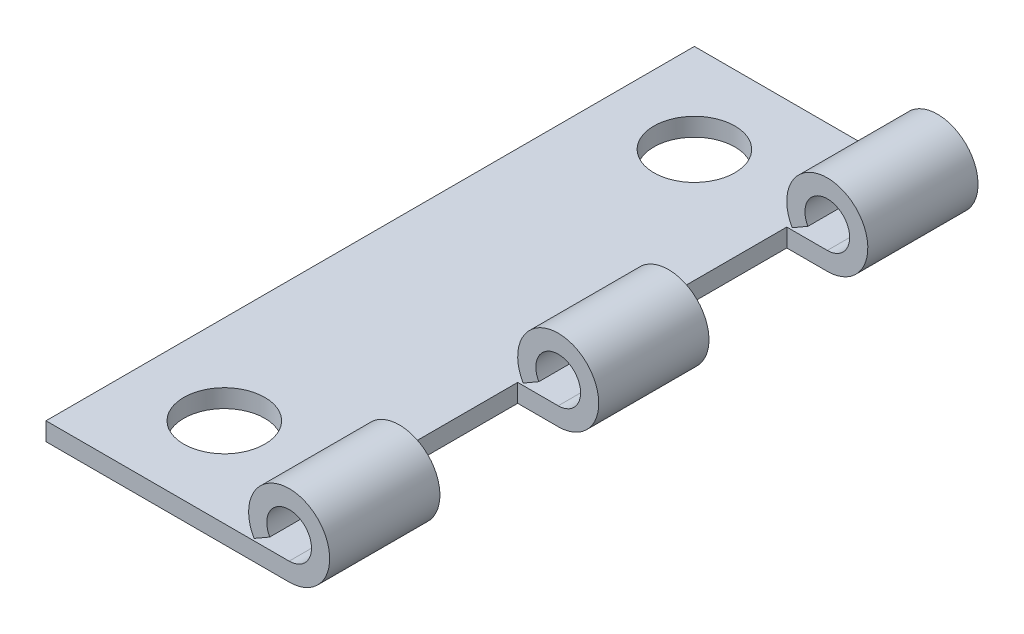
SolidWorks part; units mm, degrees
ref_plane "Front Plane" through (0, 0, 0) normal (0, 0, 1) x (1, 0, 0)
ref_plane "Top Plane" through (0, 0, 0) normal (0, 1, 0) x (1, 0, 0)
ref_plane "Right Plane" through (0, 0, 0) normal (1, 0, 0) x (0, 0, -1)
sketch "Sketch1" plane through (0, 0, 0) normal (0, 0, 1) x (1, 0, 0)
  line L0 (0, 0) -> (19.05, 0)
  line L1 (16.3004, 1.5875) -> (17.5322, 2.2987)
  line L2 (19.05, 1.4224) -> (0, 1.4224)
  line L3 (0, 1.4224) -> (0, 0)
  line L4 (19.05, 1.4224) -> (19.05, 10.3225) construction
  arc A0 (19.05, 0) -> (16.3004, 1.5875) centre (19.05, 3.175) ccw
  arc A1 (17.5322, 2.2987) -> (19.05, 1.4224) centre (19.05, 3.175) cw
  dimension "D1" = 1.4224
  dimension "D3" = 120
  dimension "D5" = 3.175
  dimension "D2" = 1.4224
  dimension "D4" = 19.05
extrude "Boss-Extrude1" add sketch "Sketch1" along normal blind 50.8
sketch "Sketch2" plane through (0, 0, 0) normal (0, -1, 0) x (1, 0, 0)
  line L0 (0, 50.8) -> (0, 0) construction
  line L1 (0, 50.8) -> (19.05, 50.8) construction
  line L2 (0, 0) -> (19.05, 0) construction
  line L3 (22.225, 0) -> (22.225, 50.8) construction
  line L4 (15.875, 50.8) -> (22.225, 50.8)
  line L5 (15.875, 50.8) -> (15.875, 42.164)
  line L6 (15.875, 42.164) -> (22.225, 42.164)
  line L7 (22.225, 50.8) -> (22.225, 42.164)
  line L8 (8.0066, 50.8) -> (8.0066, 0) construction
  line L9 (22.225, 29.718) -> (15.875, 29.718)
  line L10 (22.225, 29.718) -> (22.225, 21.082)
  line L11 (22.225, 21.082) -> (15.875, 21.082)
  line L12 (15.875, 29.718) -> (15.875, 21.082)
  line L13 (22.225, 8.636) -> (15.875, 8.636)
  line L14 (22.225, 8.636) -> (22.225, 0)
  line L15 (22.225, 0) -> (15.875, 0)
  line L16 (15.875, 8.636) -> (15.875, 0)
  line L17 (22.225, 25.4) -> (8.0066, 25.4) construction
  line L18 (15.875, 42.164) -> (15.875, 29.718)
  line L19 (22.225, 42.164) -> (22.225, 29.718)
  line L20 (15.875, 21.082) -> (15.875, 8.636)
  line L21 (22.225, 21.082) -> (22.225, 8.636)
  circle A0 centre (6.985, 43.815) radius 3.175
  circle A1 centre (6.985, 6.985) radius 3.175
  line M2 (19.05, 0) -> (19.05, 50.8)
  dimension "D1" = 6.985
  dimension "D4" = 6.35
  dimension "D2" = 6.985
  dimension "D3" = 6.985
  dimension "D5" = 50.8
  dimension "D6" = 8.636
  dimension "D7" = 6.35
extrude "Cut-Extrude1" cut sketch "Sketch2" against normal through all contours L21 L11 L13 M2 | L11 L20 L13 M2 | L19 L6 L9 M2 | L6 L18 L9 M2 | A0 | A1
equation "\"D2@Sketch1\"=\"D1@Sketch1\""
equation "\"D2@Sketch2\"=\"D1@Sketch2\""
equation "\"D3@Sketch2\"=\"D1@Sketch2\""
